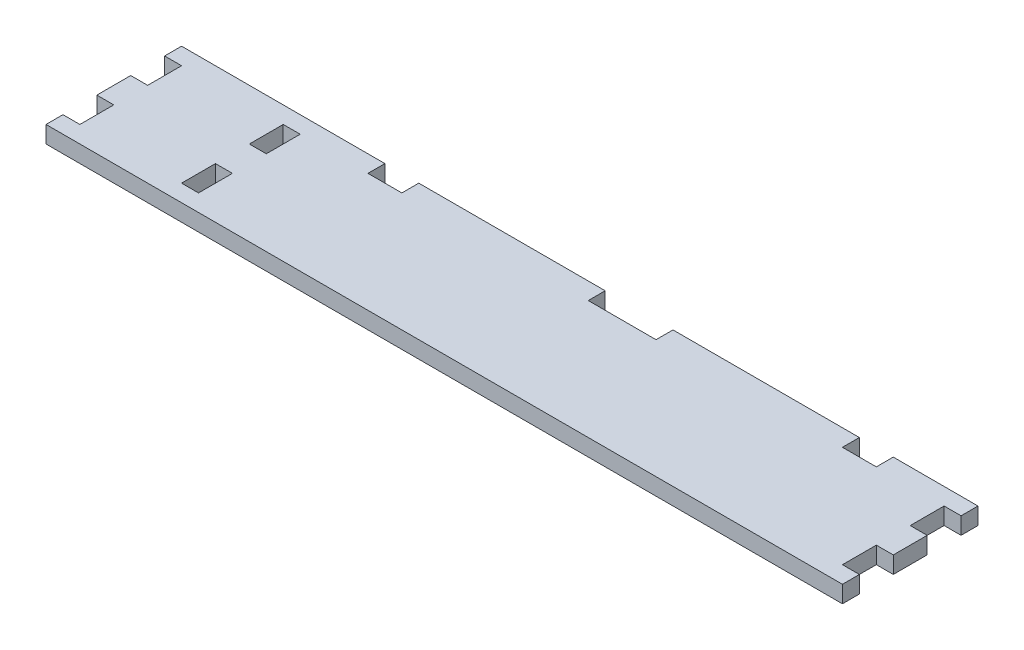
SolidWorks part; units mm, degrees
ref_plane "前视基准面" through (0, 0, 0) normal (0, 0, 1) x (1, 0, 0)
ref_plane "上视基准面" through (0, 0, 0) normal (0, 1, 0) x (1, 0, 0)
ref_plane "右视基准面" through (0, 0, 0) normal (1, 0, 0) x (0, 0, -1)
sketch "草图1" plane through (0, 0, 0) normal (0, 1, 0) x (1, 0, 0)
  line L0 (5, 48.9876) -> (5, -11.1964) construction
  line L1 (0, 0) -> (200, 0)
  line L3 (0, 40) -> (25, 40)
  line L4 (200, 0) -> (200, 5)
  line L5 (195, 54.088) -> (195, -13.8485) construction
  line L6 (-16.1732, 35) -> (205.1816, 35) construction
  line L8 (0, 35) -> (5, 35)
  line L10 (0, 25) -> (5, 25)
  line L11 (5, 35) -> (5, 25)
  line L12 (0, 15) -> (5, 15)
  line L13 (110, 40) -> (165, 40)
  line L14 (0, 5) -> (5, 5)
  line L15 (5, 15) -> (5, 5)
  line L16 (175, 40) -> (200, 40)
  line L17 (25, 40) -> (25, 35)
  line L18 (25, 35) -> (35, 35)
  line L19 (35, 40) -> (35, 35)
  line L20 (200, 15) -> (200, 25)
  line L21 (165, 40) -> (165, 35)
  line L22 (165, 35) -> (175, 35)
  line L23 (175, 40) -> (175, 35)
  line L24 (195, 35) -> (200, 35)
  line L25 (195, 35) -> (195, 25)
  line L26 (195, 25) -> (200, 25)
  line L27 (0, 0) -> (-35, 0)
  line L28 (195, 15) -> (200, 15)
  line L29 (195, 15) -> (195, 5)
  line L30 (195, 5) -> (200, 5)
  line L31 (200, 35) -> (200, 40)
  line L32 (35, 40) -> (90, 40)
  line L33 (90, 40) -> (90, 35)
  line L34 (90, 35) -> (110, 35)
  line L35 (110, 40) -> (110, 35)
  line L36 (-35, 0) -> (-35, 5)
  line L37 (-35, 5) -> (-30, 5)
  line L38 (-30, 5) -> (-30, 15)
  line L39 (-30, 15) -> (-35, 15)
  line L40 (-35, 15) -> (-35, 25)
  line L41 (-35, 25) -> (-30, 25)
  line L42 (-30, 25) -> (-30, 35)
  line L43 (-30, 35) -> (-35, 35)
  line L44 (-35, 35) -> (-35, 40)
  line L45 (-35, 40) -> (0, 40)
  line L46 (0, 35) -> (0, 25)
  line L47 (0, 15) -> (0, 5)
  point P49 (25, 37.5)
  dimension "D1" = 40
  dimension "D2" = 200
  dimension "D3" = 90
  dimension "D4" = 5
  dimension "D5" = 5
  dimension "D6" = 10
  dimension "D7" = 10
  dimension "D8" = 5
  dimension "D9" = 10
  dimension "D10" = 10
  dimension "D11" = 25
  dimension "D12" = 25
  dimension "D13" = 90
  dimension "D14" = 5
  dimension "D15" = 10
  dimension "D16" = 10
  dimension "D17" = 20
extrude "凸台-拉伸1" add sketch "草图1" along normal blind 5
